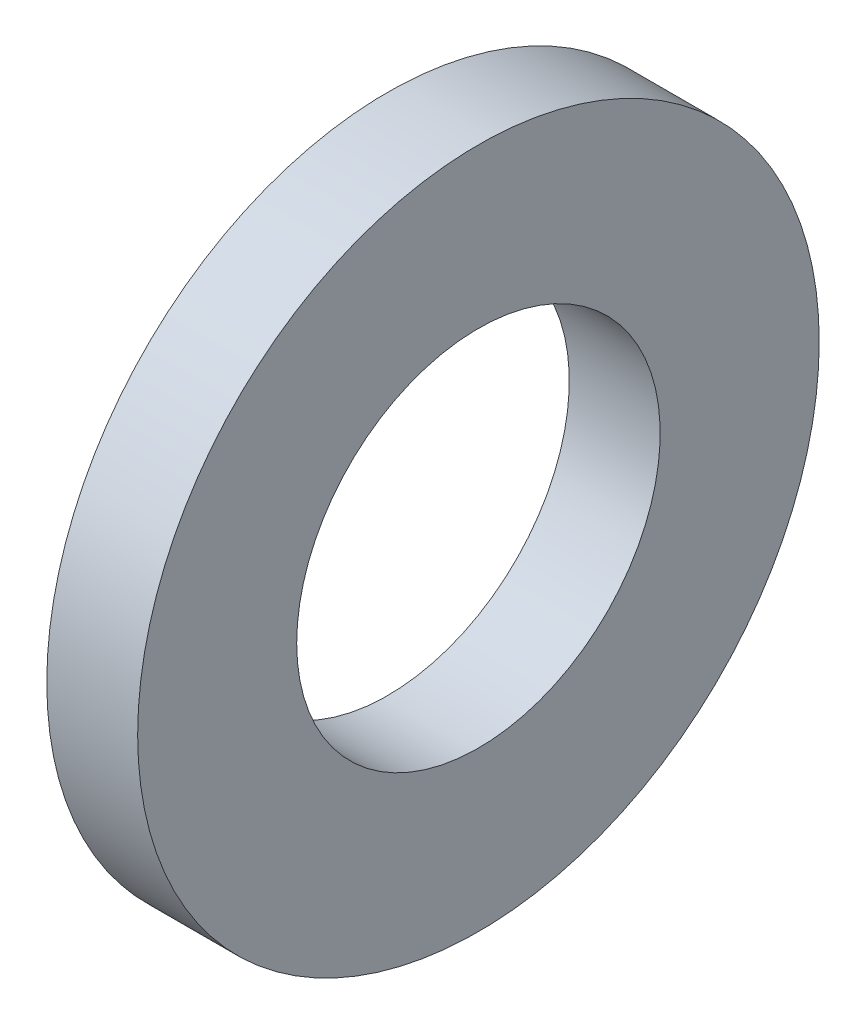
SolidWorks part; units mm, degrees
ref_plane "Plane1" through (0, 0, 0) normal (0, 0, 1) x (1, 0, 0)
ref_plane "Plane2" through (0, 0, 0) normal (0, 1, 0) x (1, 0, 0)
ref_plane "Plane3" through (0, 0, 0) normal (1, 0, 0) x (0, 0, -1)
sketch "Sketch1" plane through (0, 0, 0) normal (0, 0, 1) x (1, 0, 0)
  line L0 (-34.925, 0) -> (9.525, 0) construction
  line L1 (0, 4) -> (0, 7.5)
  line L2 (0, 7.5) -> (-2, 7.5)
  line L3 (-2, 7.5) -> (-2, 4)
  line L4 (-2, 4) -> (0, 4)
  dimension "Thickness" = 2
  dimension "Inside_dia" = 8
  dimension "Outside_dia" = 15
revolve "Base-Revolve" add sketch "Sketch1" angle 360 about L0
